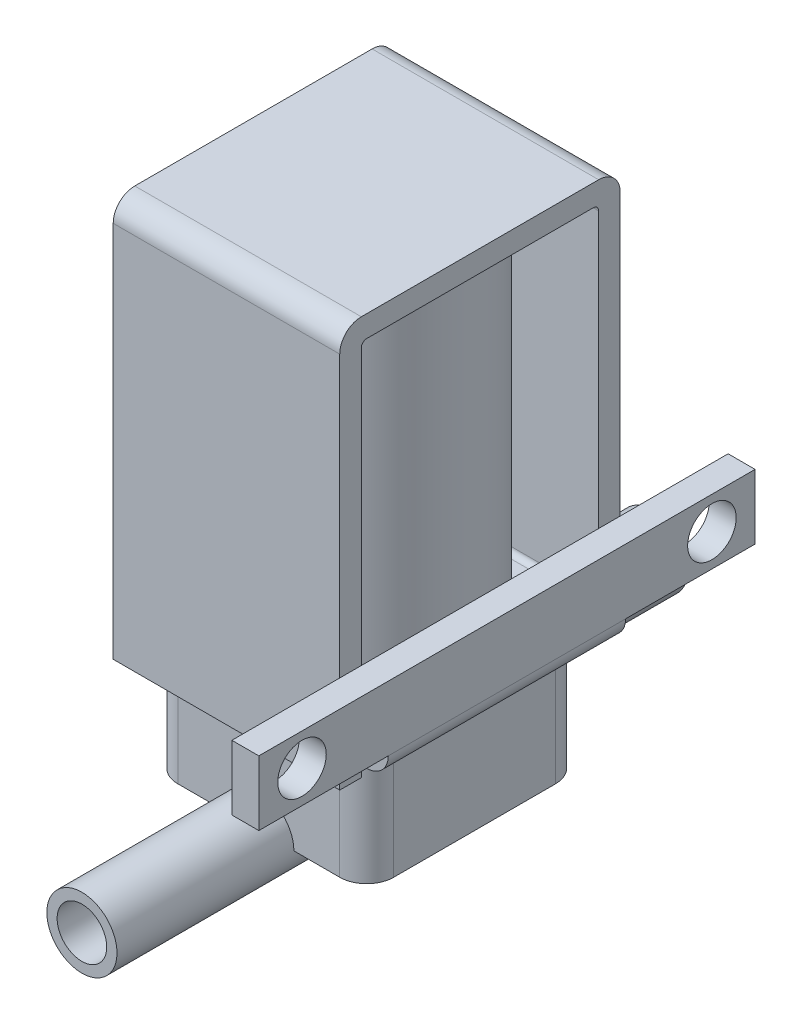
SolidWorks part; units mm, degrees
ref_plane "Front" through (0, 0, 0) normal (0, 0, 1) x (1, 0, 0)
ref_plane "Top" through (0, 0, 0) normal (0, 1, 0) x (1, 0, 0)
ref_plane "Right" through (0, 0, 0) normal (1, 0, 0) x (0, 0, -1)
sketch "Sketch1" plane through (0, 0, 0) normal (0, 1, 0) x (1, 0, 0)
  line L1 (2.5, 0) -> (17.5, 0)
  line L2 (0, 2.5) -> (0, 17.5)
  line L3 (2.5, 20) -> (17.5, 20)
  line L4 (20, 2.5) -> (20, 17.5)
  arc A0 (17.5, 20) -> (20, 17.5) centre (17.5, 17.5) cw
  arc A1 (2.5, 0) -> (0, 2.5) centre (2.5, 2.5) cw
  arc A2 (17.5, 0) -> (20, 2.5) centre (17.5, 2.5) ccw
  arc A3 (0, 17.5) -> (2.5, 20) centre (2.5, 17.5) cw
  point P9 (0, 0)
  point P12 (20, 0)
  point P15 (0, 20)
  dimension "D3" = 2.5
  dimension "D1" = 20
  dimension "D2" = 20
extrude "Boss-Extrude1" add sketch "Sketch1" along normal blind 11
sketch "Sketch2" plane through (0, 0, 0) normal (0, 0, 1) x (1, 0, 0)
  line L0 (2.5, 0) -> (17.5, 0) construction
  circle A0 centre (10, 0) radius 3.25
  dimension "D1" = 6.5
extrude "Boss-Extrude2" add sketch "Sketch2" along normal blind 16.4 and the other way up to vertex (17.5 mm away)
sketch "Sketch3" plane through (0, 0, 16.4) normal (0, 0, 1) x (1, 0, 0)
  circle A0 centre (10, 0) radius 2.3
  dimension "D1" = 4.6
extrude "Cut-Extrude1" cut sketch "Sketch3" against normal offset from surface (28.9 mm away) 5 up to face at (10, -1.625, -17.5)
sketch "Sketch4" plane through (0, 0, -20) normal (0, 0, -1) x (-1, 0, 0)
  line L0 (-17.5, 0) -> (-2.5, 0) construction
  circle A0 centre (-10, 4.25) radius 3.25
  dimension "D1" = 6.5
  dimension "D2" = 4.25
extrude "Boss-Extrude3" add sketch "Sketch4" along normal blind 16.5
sketch "Sketch5" plane through (0, 0, -36.5) normal (0, 0, -1) x (-1, 0, 0)
  circle A0 centre (-10, 4.25) radius 2.3
  dimension "D1" = 4.6
extrude "Cut-Extrude2" cut sketch "Sketch5" against normal blind 28
sketch "Sketch7" plane through (20, 0, 0) normal (1, 0, 0) x (0, 0, -1)
  line L0 (2.5, 11) -> (17.5, 11) construction
  line L1 (-1, 11) -> (21, 11)
  line L2 (-3, 10) -> (-3, 45)
  line L3 (-1, 47) -> (21, 47)
  line L4 (23, 10) -> (23, 45)
  line L5 (-0.5, 13) -> (20.5, 13)
  line L8 (-3, 10) -> (-1, 10)
  line L9 (-1, 11) -> (-1, 10)
  line L12 (23, 10) -> (21, 10)
  line L13 (21, 11) -> (21, 10)
  line L14 (21, 13.5) -> (21, 44.5)
  line L15 (20.5, 45) -> (-0.5, 45)
  line L16 (-1, 44.5) -> (-1, 13.5)
  arc A0 (21, 47) -> (23, 45) centre (21, 45) cw
  arc A1 (-3, 45) -> (-1, 47) centre (-1, 45) cw
  arc A2 (20.5, 45) -> (21, 44.5) centre (20.5, 44.5) cw
  arc A3 (-0.5, 45) -> (-1, 44.5) centre (-0.5, 44.5) ccw
  arc A4 (20.5, 13) -> (21, 13.5) centre (20.5, 13.5) ccw
  arc A5 (-0.5, 13) -> (-1, 13.5) centre (-0.5, 13.5) cw
  point P4 (10, 11)
  dimension "D9" = 2
  dimension "D10" = 0.5
  dimension "D11" = 0.5
  dimension "D1" = 26
  dimension "D2" = 2
  dimension "D3" = 1
  dimension "D4" = 1
  dimension "D5" = 2
  dimension "D6" = 2
  dimension "D7" = 37
  dimension "D8" = 22
extrude "Boss-Extrude4" add sketch "Sketch7" against normal offset from surface (21 mm away) 0.5 from offset 0.5
sketch "Sketch8" plane through (0, 13, 0) normal (0, 1, 0) x (1, 0, 0)
  line L0 (-0.5, 21) -> (20.5, 21) construction
  line L2 (20.5, -0.5) -> (20.5, 20.5) construction
  circle A0 centre (10, 10) radius 9.5
  dimension "D3" = 19
  dimension "D1" = 11
  dimension "D2" = 10.5
extrude "Boss-Extrude5" add sketch "Sketch8" along normal up to surface (32 mm away) up to face at (10, 45, -10)
sketch "Sketch10" plane through (20.5, 0, 0) normal (1, 0, 0) x (0, 0, -1)
  line L0 (10, 19) -> (10, 11) construction
  line L1 (-13, 19) -> (33, 19)
  line L2 (-13, 19) -> (-13, 13)
  line L3 (-1, 11) -> (21, 11)
  line L4 (33, 19) -> (33, 13)
  line L5 (-0.5, 13) -> (20.5, 13) construction
  line L6 (21, 10) -> (23, 10) construction
  line L9 (-1, 11) -> (-1, 13)
  line L10 (-1, 13) -> (-13, 13)
  line L13 (21, 11) -> (21, 13)
  line L14 (21, 13) -> (33, 13)
  circle A0 centre (-9, 16) radius 2.25
  circle A1 centre (29, 15.9987) radius 2.25
  point P5 (10, 13)
  dimension "D4" = 4.5
  dimension "D1" = 46
  dimension "D2" = 8
  dimension "D3" = 1
  dimension "D5" = 38
  dimension "D6" = 4
  dimension "D7" = 3
  dimension "D8" = 3.0013
  dimension "D9" = 2
  dimension "D10" = 2
  dimension "D11" = 22
extrude "Boss-Extrude6" add sketch "Sketch10" along normal blind 2.5
fillet "Fillet1" radius 2 1 edges at (23, 11, -10)
